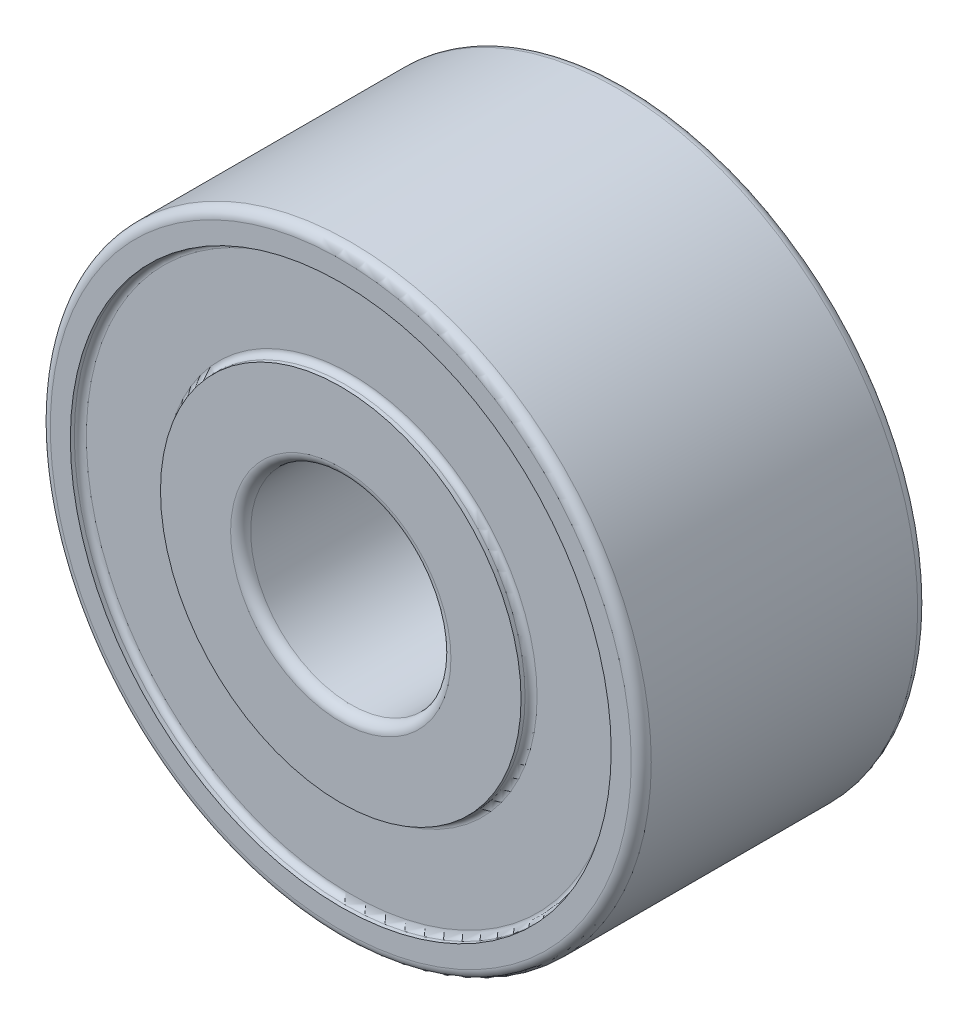
SolidWorks part; units mm, degrees
ref_plane "Ebene vorne" through (0, 0, 0) normal (0, 0, 1) x (1, 0, 0)
ref_plane "Ebene oben" through (0, 0, 0) normal (0, 1, 0) x (1, 0, 0)
ref_plane "Ebene rechts" through (0, 0, 0) normal (1, 0, 0) x (0, 0, -1)
sketch "Skizze1" plane through (0, 0, 0) normal (0, 0, 1) x (1, 0, 0)
  circle A0 centre (0, 0) radius 15
  circle A1 centre (0, 0) radius 5
extrude "Aufsatz-Linear austragen1" add sketch "Skizze1" along normal blind 14.3
fillet "Verrundung1" radius 0.5 4 edges at (5, 0, 0) (15, 0, 0) (5, 0, 14.3) (15, 0, 14.3)
sketch "Skizze2" plane through (0, 0, 0) normal (0, 0, -1) x (-1, 0, 0)
  circle A0 centre (0, 0) radius 13.5
  circle A1 centre (0, 0) radius 9
  dimension "D1" = 18
  dimension "D2" = 27
extrude "Schnitt-Linear austragen1" cut sketch "Skizze2" against normal blind 0.5
sketch "Skizze3" plane through (0, 0, 14.3) normal (0, 0, 1) x (1, 0, 0)
  circle A0 centre (0, 0) radius 9
  circle A1 centre (0, 0) radius 13.5
extrude "Schnitt-Linear austragen2" cut sketch "Skizze3" against normal blind 0.5
fillet "Verrundung2" radius 0.3 4 edges at (13.5, 0, 13.8) (9, 0, 13.8) (-13.5, 0, 0.5) (-9, 0, 0.5)
